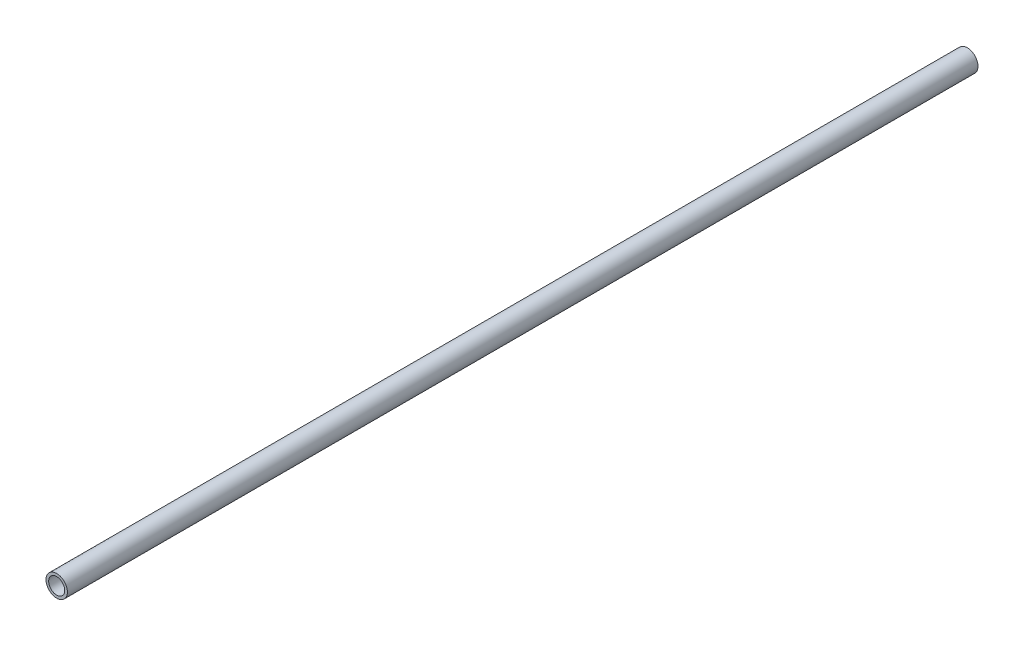
SolidWorks part; units mm, degrees
ref_plane "前视基准面" through (0, 0, 0) normal (0, 0, 1) x (1, 0, 0)
ref_plane "上视基准面" through (0, 0, 0) normal (0, 1, 0) x (1, 0, 0)
ref_plane "右视基准面" through (0, 0, 0) normal (1, 0, 0) x (0, 0, -1)
other "Configuration Table"
sketch "草图1" plane through (0, 0, 0) normal (0, 0, 1) x (1, 0, 0)
  circle A0 centre (0, 0) radius 4
  circle A1 centre (0, 0) radius 3
  dimension "D1" = 6
  dimension "D2" = 8
extrude "凸台-拉伸1" add sketch "草图1" along normal blind 340
